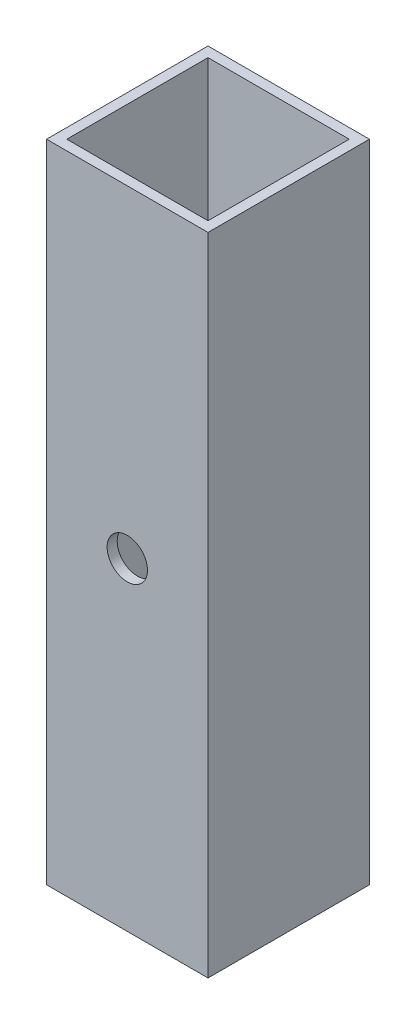
SolidWorks part; units mm, degrees
ref_plane "Front Plane" through (0, 0, 0) normal (0, 0, 1) x (1, 0, 0)
ref_plane "Top Plane" through (0, 0, 0) normal (0, 1, 0) x (1, 0, 0)
ref_plane "Right Plane" through (0, 0, 0) normal (1, 0, 0) x (0, 0, -1)
sketch "Sketch1" plane through (0, 0, 0) normal (0, 1, 0) x (1, 0, 0)
  line L1 (12.7, 12.7) -> (-12.7, 12.7)
  line L2 (12.7, 12.7) -> (12.7, -12.7)
  line L3 (12.7, -12.7) -> (-12.7, -12.7)
  line L4 (-12.7, 12.7) -> (-12.7, -12.7)
  line L5 (12.7, 12.7) -> (-12.7, -12.7) construction
  line L6 (12.7, -12.7) -> (-12.7, 12.7) construction
  line L7 (-11.1125, -11.1125) -> (11.1125, -11.1125)
  line L8 (-11.1125, -11.1125) -> (-11.1125, 11.1125)
  line L9 (-11.1125, 11.1125) -> (11.1125, 11.1125)
  line L10 (11.1125, -11.1125) -> (11.1125, 11.1125)
  line L11 (-11.1125, -11.1125) -> (11.1125, 11.1125) construction
  line L12 (-11.1125, 11.1125) -> (11.1125, -11.1125) construction
  point P0 (0, 0)
  point P6 (0, 0)
  dimension "D1" = 25.4
  dimension "D2" = 25.4
  dimension "D3" = 1.5875
  dimension "D4" = 1.5875
extrude "Boss-Extrude1" add sketch "Sketch1" along normal blind 101.6
sketch "Sketch2" plane through (0, 0, 12.7) normal (0, 0, 1) x (1, 0, 0)
  line L0 (-12.7, 0) -> (12.7, 0) construction
  line L1 (-12.7, 101.6) -> (-12.7, 0) construction
  circle A0 centre (0, 50.8) radius 3.175
  dimension "D1" = 6.35
  dimension "D2" = 50.8
  dimension "D3" = 12.7
extrude "Cut-Extrude1" cut sketch "Sketch2" against normal through all
